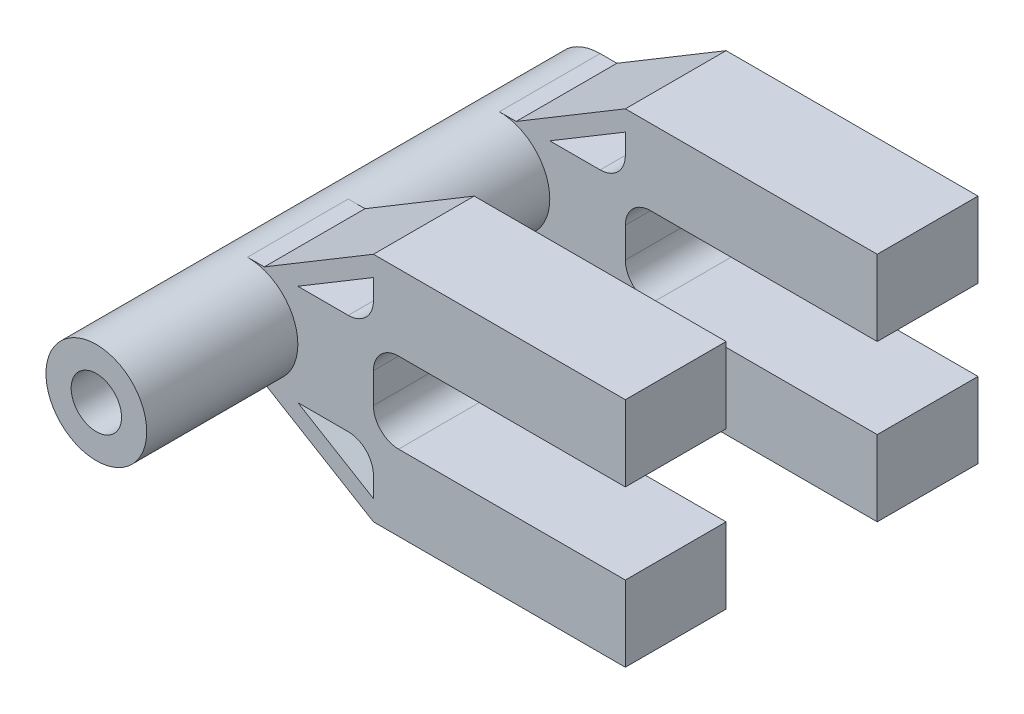
SolidWorks part; units mm, degrees
ref_plane "정면" through (0, 0, 0) normal (0, 0, 1) x (1, 0, 0)
ref_plane "윗면" through (0, 0, 0) normal (0, 1, 0) x (1, 0, 0)
ref_plane "우측면" through (0, 0, 0) normal (1, 0, 0) x (0, 0, -1)
sketch "스케치1" plane through (0, 0, 0) normal (0, 0, 1) x (1, 0, 0)
  circle A0 centre (0, 0) radius 20
  dimension "D1" = 40
extrude "보스-돌출1" add sketch "스케치1" along normal blind 200
sketch "스케치2" plane through (0, 0, 0) normal (1, 0, 0) x (0, 0, -1)
  line L0 (-200, -20) -> (0, -20) construction
  line L1 (0, 20) -> (-40, 20)
  line L2 (0, 20) -> (0, -20)
  line L3 (0, -20) -> (-40, -20)
  line L4 (-40, 20) -> (-40, -20)
  line L5 (0, 20) -> (-200, 20) construction
  line L6 (-100, 20) -> (-140, 20)
  line L7 (-100, 20) -> (-100, -20)
  line L8 (-100, -20) -> (-140, -20)
  line L9 (-140, 20) -> (-140, -20)
extrude "보스-돌출2" add sketch "스케치2" along normal blind 50
sketch "스케치3" plane through (0, 0, 0) normal (0, 0, -1) x (-1, 0, 0)
  line L0 (-50, -20) -> (-50, 20) construction
  line L1 (-50, -46) -> (-150, -46)
  line L2 (-50, -46) -> (-50, -16)
  line L3 (-50, -16) -> (-150, -16)
  line L4 (-150, -46) -> (-150, -16)
  line L5 (-50, 16) -> (-150, 16)
  line L6 (-50, 16) -> (-50, 46)
  line L7 (-50, 46) -> (-150, 46)
  line L8 (-150, 16) -> (-150, 46)
  line L9 (-50, 20) -> (0, 20) construction
  point P10 (-50, 0)
  dimension "D1" = 32
  dimension "D2" = 20
  dimension "D3" = 16
  dimension "D4" = 100
  dimension "D5" = 100
  dimension "D6" = 30
  dimension "D7" = 30
extrude "보스-돌출3" add sketch "스케치3" against normal blind 40
sketch "스케치4" plane through (0, 0, 100) normal (0, 0, -1) x (-1, 0, 0)
  line L0 (-50, -46) -> (-150, -46)
  line L1 (-50, -46) -> (-50, -16)
  line L2 (-50, -16) -> (-150, -16)
  line L3 (-150, -46) -> (-150, -16)
  line L4 (-50, 16) -> (-150, 16)
  line L5 (-50, 16) -> (-50, 46)
  line L6 (-50, 46) -> (-150, 46)
  line L7 (-150, 16) -> (-150, 46)
  line L8 (-50, -16) -> (-50, 16) construction
  point P14 (-50, 0)
  dimension "D1" = 32
  dimension "D3" = 100
  dimension "D4" = 100
  dimension "D5" = 30
  dimension "D6" = 30
  dimension "D7" = 16
extrude "보스-돌출4" add sketch "스케치4" against normal blind 40
fillet "필렛1" radius 10 8 edges at (50, -16, 120) (50, -20, 120) (50, -20, 20) (50, -16, 20) (50, 16, 120) (50, 16, 20) (50, 20, 120) (50, 20, 20)
ref_plane "평면1" through (0, 0, 20) normal (0, 0, 1) x (1, 0, 0)
sketch "스케치10" plane through (0, 0, 200) normal (0, 0, 1) x (1, 0, 0)
  circle A0 centre (0, 0) radius 10
  dimension "D1" = 20
extrude "컷-돌출1" cut sketch "스케치10" against normal blind 20
sketch "스케치11" plane through (0, 0, 20) normal (0, 0, 1) x (1, 0, 0)
  line L0 (20, 20) -> (50, 38)
  line L1 (40, 20) -> (0, 20) construction
  line L2 (50, 30) -> (50, 46) construction
  line L3 (50, 46) -> (6.6667, 20)
  line L4 (20, -20) -> (50, -38)
  line L5 (40, -20) -> (0, -20) construction
  line L6 (50, -46) -> (50, -30) construction
  line L7 (6.6667, -20) -> (50, -46)
  line L8 (50, 46) -> (50, 38)
  line L9 (20, 20) -> (6.6667, 20)
  line L10 (20, -20) -> (6.6667, -20)
  line L11 (50, -46) -> (50, -38)
extrude "보스-돌출6" add sketch "스케치11" along normal mid plane 40
ref_plane "평면2" through (0, 0, 120) normal (0, 0, 1) x (1, 0, 0)
sketch "스케치13" plane through (0, 0, 120) normal (0, 0, 1) x (1, 0, 0)
  line L0 (20, 20) -> (50, 38)
  line L1 (40, 20) -> (0, 20) construction
  line L2 (50, 30) -> (50, 46) construction
  line L3 (50, 38) -> (50, 46)
  line L4 (50, 46) -> (6.6667, 20)
  line L5 (6.6667, 20) -> (20, 20)
  line L6 (20, -20) -> (6.6667, -20)
  line L7 (40, -20) -> (0, -20) construction
  line L8 (6.6667, -20) -> (50, -46)
  line L9 (50, -46) -> (50, -38)
  line L10 (50, -46) -> (50, -30) construction
  line L11 (50, -38) -> (20, -20)
extrude "보스-돌출7" add sketch "스케치13" along normal mid plane 40
